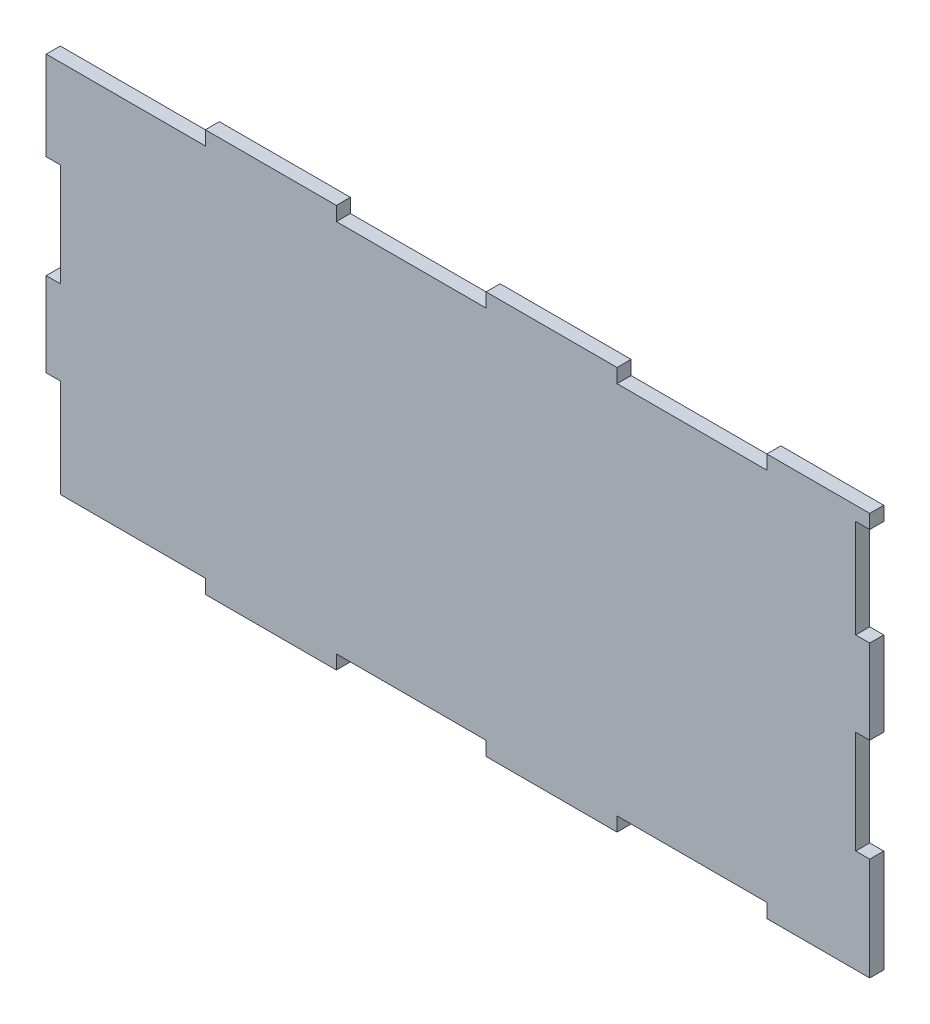
SolidWorks part; units mm, degrees
ref_plane "Plan de face" through (0, 0, 0) normal (0, 0, 1) x (1, 0, 0)
ref_plane "Plan de dessus" through (0, 0, 0) normal (0, 1, 0) x (1, 0, 0)
ref_plane "Plan de droite" through (0, 0, 0) normal (1, 0, 0) x (0, 0, -1)
sketch "Esquisse1" plane through (0, 0, 0) normal (0, 0, 1) x (1, 0, 0)
  line L1 (-44.5891, 57.4744) -> (125.4109, 57.4744)
  line L2 (-44.5891, 57.4744) -> (-44.5891, -22.5256)
  line L3 (-44.5891, -22.5256) -> (125.4109, -22.5256)
  line L4 (125.4109, 57.4744) -> (125.4109, -22.5256)
  dimension "D1" = 80
  dimension "D2" = 170
extrude "Boss.-Extru.1" add sketch "Esquisse1" along normal blind 3
sketch "Esquisse3" plane through (0, 0, 0) normal (0, 0, -1) x (-1, 0, 0)
  line L0 (-125.4109, 57.4744) -> (44.5891, 57.4744) construction
  line L1 (44.5891, 57.4744) -> (44.5891, -22.5256) construction
  line L2 (44.5891, -22.5256) -> (-125.4109, -22.5256) construction
  line L3 (-125.4109, -22.5256) -> (-125.4109, 57.4744) construction
  line L4 (-106.4109, 57.4744) -> (-151.449, 57.4744) construction
  line L5 (13.5891, 57.4744) -> (-14.4109, 57.4744)
  line L6 (13.5891, 57.4744) -> (13.5891, 60.4744)
  line L7 (13.5891, 60.4744) -> (-14.4109, 60.4744)
  line L8 (-14.4109, 57.4744) -> (-14.4109, 60.4744)
  line L9 (-46.4109, 57.4744) -> (-74.4109, 57.4744)
  line L10 (-46.4109, 57.4744) -> (-46.4109, 60.4744)
  line L11 (-46.4109, 60.4744) -> (-74.4109, 60.4744)
  line L12 (-74.4109, 57.4744) -> (-74.4109, 60.4744)
  line L13 (44.5891, 17.4744) -> (-139.0269, 17.4744) construction
  line L14 (-106.4109, 57.4744) -> (-128.4109, 57.4744)
  line L15 (-106.4109, 57.4744) -> (-106.4109, 60.4744)
  line L16 (-106.4109, 60.4744) -> (-128.4109, 60.4744)
  line L17 (-128.4109, 57.4744) -> (-128.4109, 60.4744)
  line L18 (-106.4109, -25.5256) -> (-128.4109, -25.5256)
  line L19 (-128.4109, -22.5256) -> (-128.4109, -25.5256)
  line L20 (-106.4109, -22.5256) -> (-128.4109, -22.5256)
  line L21 (-106.4109, -22.5256) -> (-106.4109, -25.5256)
  line L22 (-46.4109, -25.5256) -> (-74.4109, -25.5256)
  line L23 (-74.4109, -22.5256) -> (-74.4109, -25.5256)
  line L24 (-46.4109, -22.5256) -> (-74.4109, -22.5256)
  line L25 (-46.4109, -22.5256) -> (-46.4109, -25.5256)
  line L26 (13.5891, -25.5256) -> (-14.4109, -25.5256)
  line L27 (-14.4109, -22.5256) -> (-14.4109, -25.5256)
  line L28 (13.5891, -22.5256) -> (-14.4109, -22.5256)
  line L29 (13.5891, -22.5256) -> (13.5891, -25.5256)
  point P4 (13.5891, 57.4744)
  point P9 (-14.4109, 57.4744)
  point P10 (-46.4109, 57.4744)
  point P11 (-74.4109, 57.4744)
  point P12 (-106.4109, 57.4744)
  point P23 (-128.4109, 57.4744)
  dimension "D1" = 31
  dimension "D2" = 28
  dimension "D3" = 32
  dimension "D4" = 28
  dimension "D5" = 32
  dimension "D6" = 3
  dimension "D7" = 3
  dimension "D8" = 3
  dimension "D9" = 3
extrude "Boss.-Extru.2" add sketch "Esquisse3" against normal blind 3
sketch "Esquisse4" plane through (0, 0, 3) normal (0, 0, 1) x (1, 0, 0)
  line L0 (125.4109, -22.5256) -> (125.4109, 57.4744) construction
  line L1 (-44.5891, -22.5256) -> (-44.5891, 57.4744) construction
  line L3 (125.4109, -3.5256) -> (128.4109, -3.5256)
  line L4 (125.4109, -3.5256) -> (125.4109, -22.5256)
  line L5 (125.4109, -22.5256) -> (128.4109, -22.5256)
  line L6 (128.4109, -3.5256) -> (128.4109, -22.5256)
  line L7 (125.4109, 36.4744) -> (128.4109, 36.4744)
  line L8 (125.4109, 36.4744) -> (125.4109, 18.4744)
  line L9 (125.4109, 18.4744) -> (128.4109, 18.4744)
  line L10 (128.4109, 36.4744) -> (128.4109, 18.4744)
  line L11 (-44.5891, 38.4744) -> (-47.5891, 38.4744)
  line L12 (-44.5891, 38.4744) -> (-44.5891, 57.7084)
  line L13 (-44.5891, 57.7084) -> (-47.5891, 57.7084)
  line L14 (-47.5891, 38.4744) -> (-47.5891, 57.7084)
  line L15 (-44.5891, -1.5256) -> (-47.5891, -1.5256)
  line L16 (-44.5891, -1.5256) -> (-44.5891, 16.4744)
  line L17 (-44.5891, 16.4744) -> (-47.5891, 16.4744)
  line L18 (-47.5891, -1.5256) -> (-47.5891, 16.4744)
  point P8 (125.4109, 36.4744)
  point P9 (125.4109, 18.4744)
  point P10 (-44.5891, 38.4744)
  point P11 (-44.5891, 16.4744)
  point P12 (125.4109, -3.5256)
  point P22 (-44.5891, -1.5256)
  point P23 (-44.5891, 48.9716)
  dimension "D1" = 21
  dimension "D2" = 18
  dimension "D3" = 22
  dimension "D4" = 21
  dimension "D5" = 18
  dimension "D6" = 22
  dimension "D7" = 3
  dimension "D8" = 3
extrude "Boss.-Extru.3" add sketch "Esquisse4" against normal blind 3
sketch "Esquisse5" plane through (0, 0, 0) normal (0, 0, -1) x (-1, 0, 0)
  line L0 (13.5891, 57.4744) -> (63.8966, 57.4744) construction
  line L2 (44.5891, 57.4744) -> (47.6604, 57.4744)
  line L3 (44.5891, 57.4744) -> (44.5891, 57.7899)
  line L4 (44.5891, 57.7899) -> (47.6604, 57.7899)
  line L5 (47.6604, 57.4744) -> (47.6604, 57.7899)
extrude "Enlèv. mat.-Extru.1" cut sketch "Esquisse5" against normal blind 3
